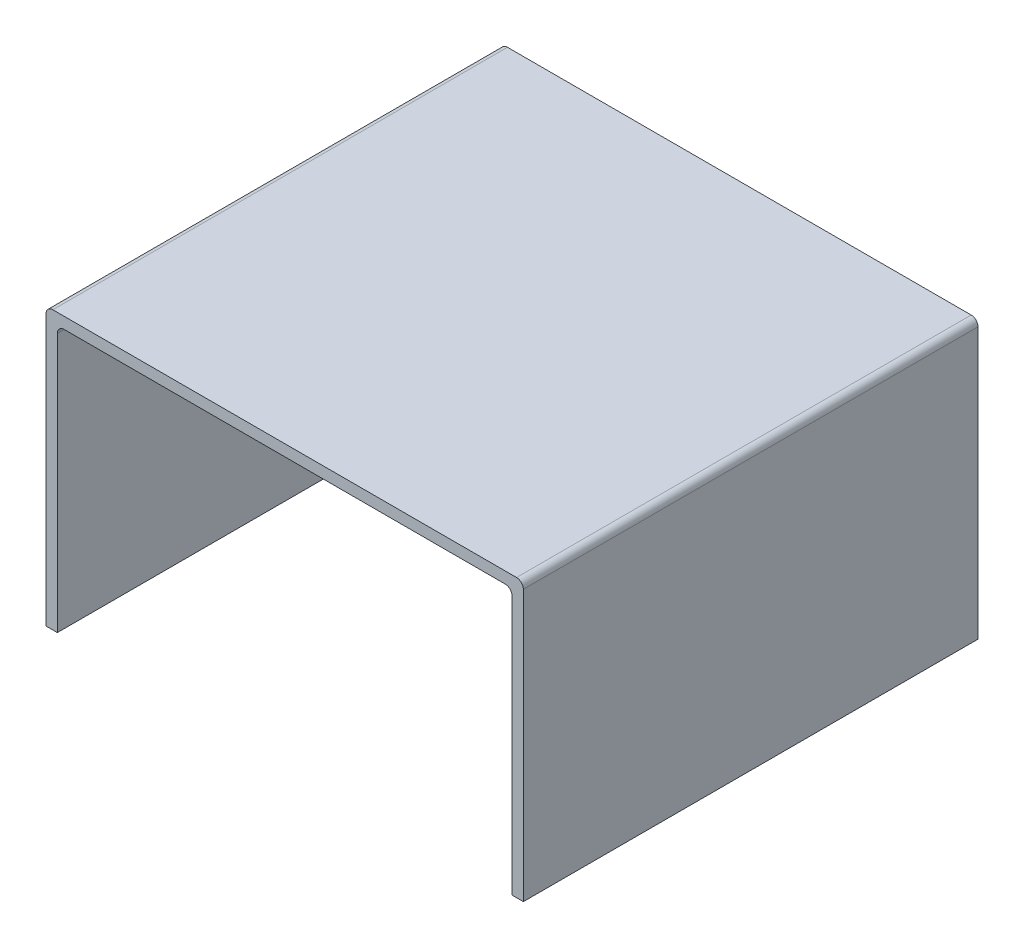
SolidWorks part; units mm, degrees
ref_plane "Front Plane" through (0, 0, 0) normal (0, 0, 1) x (1, 0, 0)
ref_plane "Top Plane" through (0, 0, 0) normal (0, 1, 0) x (1, 0, 0)
ref_plane "Right Plane" through (0, 0, 0) normal (1, 0, 0) x (0, 0, -1)
sketch "Sketch1" plane through (0, 0, 0) normal (0, 0, 1) x (1, 0, 0)
  line L0 (0, 0) -> (317.1677, 0) construction
  line L1 (0, 0) -> (0, 224.472) construction
  line L2 (0, 0) -> (0, 119)
  line L3 (3, 122) -> (207, 122)
  line L4 (210, 119) -> (210, 0)
  line L5 (210, 0) -> (205, 0)
  line L6 (0, 117) -> (317.1677, 117) construction
  line L7 (205, 0) -> (205, 114)
  line L8 (202, 117) -> (8, 117)
  line L9 (5, 114) -> (5, 0)
  line L10 (5, 0) -> (0, 0)
  arc A0 (0, 119) -> (3, 122) centre (3, 119) cw
  arc A1 (207, 122) -> (210, 119) centre (207, 119) cw
  arc A2 (205, 114) -> (202, 117) centre (202, 114) ccw
  arc A3 (8, 117) -> (5, 114) centre (8, 114) ccw
  point P19 (205, 117)
  point P22 (5, 117)
  dimension "D6" = 3
  dimension "D1" = 200
  dimension "D2" = 5
  dimension "D3" = 5
  dimension "D4" = 5
  dimension "D5" = 117
extrude "Boss-Extrude1" add sketch "Sketch1" along normal blind 200
